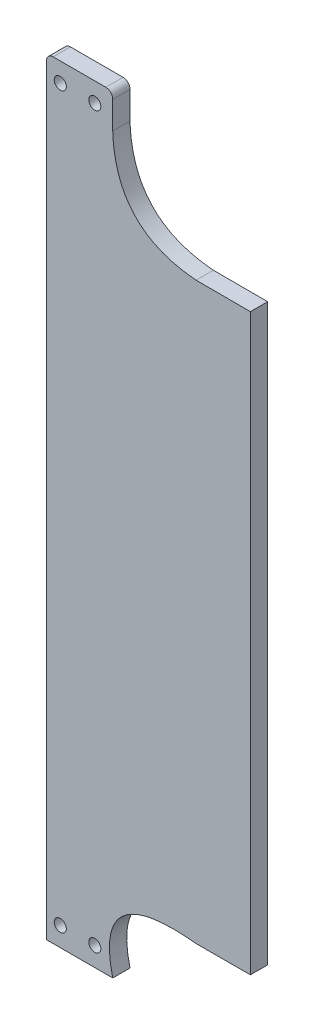
SolidWorks part; units mm, degrees
ref_plane "Front Plane" through (0, 0, 0) normal (0, 0, 1) x (1, 0, 0)
ref_plane "Top Plane" through (0, 0, 0) normal (0, 1, 0) x (1, 0, 0)
ref_plane "Right Plane" through (0, 0, 0) normal (1, 0, 0) x (0, 0, -1)
sketch "Sketch1" plane through (0, 0, 0) normal (0, 0, 1) x (1, 0, 0)
  line L1 (3.9276, -314) -> (1.9276, -314)
  line L2 (-13.3098, -314) -> (-15.3098, -314)
  line L4 (-4.4817, -314) -> (-2.4468, -314) construction
  line L13 (3.9193, -101.5) -> (3.9276, -93.5021)
  line L14 (1.9276, -91.5) -> (-13.3098, -91.5)
  line L15 (-15.3098, -93.5) -> (-15.3098, -106.1282)
  line L16 (-15.3098, -106.1282) -> (-15.3098, -314)
  line L17 (28.0656, -126.8258) -> (43.8098, -126.8636)
  line L18 (43.8098, -126.8636) -> (43.8098, -293.2646)
  line L19 (32.7887, -121.8371) -> (38.1458, -121.85) construction
  line L20 (-32.7286, -210.0641) -> (19.3929, -210.0641) construction
  line L21 (28.0656, -293.3025) -> (43.8098, -293.2646)
  line L23 (1.9276, -314) -> (-13.3098, -314)
  arc A0 (3.9276, -93.5021) -> (1.9276, -91.5) centre (1.9276, -93.5) ccw
  arc A1 (-13.3098, -91.5) -> (-15.3098, -93.5) centre (-13.3098, -93.5) ccw
  circle A2 centre (-11.2752, -97.0938) radius 1.75
  circle A3 centre (-1.2752, -97.0938) radius 1.75
  circle A4 centre (-1.2752, -308.4062) radius 1.75
  circle A5 centre (-11.2752, -308.4062) radius 1.75
  spline S0 degree 2 poles (3.9193, -101.5) (4.762, -124.979) (28.0656, -126.8258) knots 0 0 0 1 1 1
  spline S1 degree 2 poles (3.9276, -314) (-1.9436, -290.0626) (28.0656, -293.3025) knots 0 0 0 1 1 1
  point P38 (43.8098, -210.0641)
  point P39 (-15.3098, -210.0641)
  dimension "D2" = 2
  dimension "D3" = 3.5
  dimension "D4" = 3.5
  dimension "D5" = 10
  dimension "D6" = 3.5
  dimension "D7" = 3.5
  dimension "D1" = 5
  dimension "D8" = 10
  dimension "D9" = 5.5938
  dimension "D10" = 19.2374
extrude "Boss-Extrude1" add sketch "Sketch1" along normal blind 5
